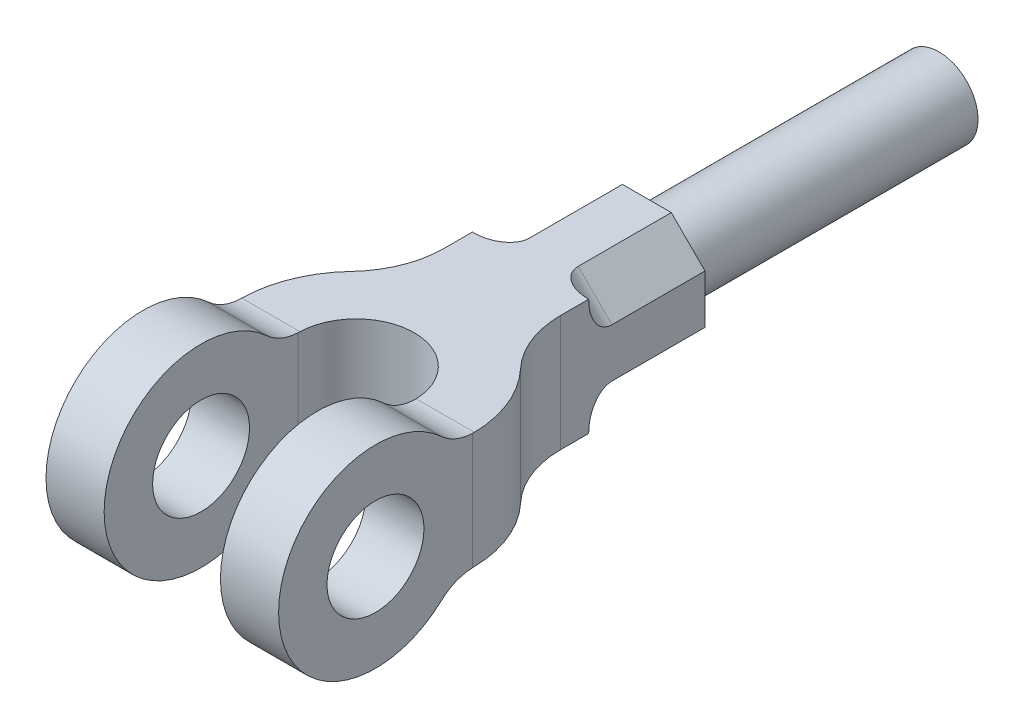
SolidWorks part; units mm, degrees
ref_plane "Front Plane" through (0, 0, 0) normal (0, 0, 1) x (1, 0, 0)
ref_plane "Top Plane" through (0, 0, 0) normal (0, 1, 0) x (1, 0, 0)
ref_plane "Right Plane" through (0, 0, 0) normal (1, 0, 0) x (0, 0, -1)
sketch "Sketch1" plane through (0, 0, 0) normal (0, 1, 0) x (1, 0, 0)
  line L1 (0, 0) -> (120, 0)
  line L2 (0, 0) -> (0, -250)
  line L3 (0, -250) -> (120, -250)
  line L4 (120, 0) -> (120, -250)
  dimension "D1" = 120
  dimension "D2" = 250
extrude "Boss-Extrude1" add sketch "Sketch1" along normal blind 100
sketch "Sketch2" plane through (0, 100, 0) normal (0, 1, 0) x (1, 0, 0)
  line L0 (60, 0) -> (60, -247.1801) construction
  line L1 (120, 0) -> (0, 0) construction
  line L2 (30, 0) -> (30, -74.5017)
  line L3 (90, 0) -> (90, -74.5017)
  line L4 (30, -150) -> (30, -250)
  line L5 (90, -150) -> (90, -250)
  line L8 (0, 0) -> (0, -250)
  line L9 (0, -250) -> (120, -250)
  line L10 (120, -250) -> (120, 0)
  line L11 (120, 0) -> (0, 0)
  line L12 (0, 0) -> (0, -250)
  line L13 (0, -250) -> (120, -250)
  line L14 (120, -250) -> (120, 0)
  line L15 (120, 0) -> (0, 0)
  arc A0 (16.3636, -108.8191) -> (103.6364, -108.8191) centre (60, -150) ccw
  arc A1 (90, -150) -> (30, -150) centre (60, -150) ccw
  arc A2 (90, -74.5017) -> (103.6364, -108.8191) centre (140, -74.5017) ccw
  arc A3 (30, -74.5017) -> (16.3636, -108.8191) centre (-20, -74.5017) cw
  point P15 (90, -98.0385)
  point P19 (30, -98.0385)
  dimension "D1" = 120
  dimension "D2" = 60
  dimension "D6" = 50
  dimension "D3" = 150
  dimension "D4" = 30
  dimension "D5" = 0
extrude "Cut-Extrude1" cut sketch "Sketch2" against normal through all
sketch "Sketch4" plane through (120, 0, 0) normal (1, 0, 0) x (0, 0, -1)
  line L0 (-250, 100) -> (-150, 100) construction
  line L1 (-250, 100) -> (-250, 0) construction
  line L2 (-250, 0) -> (-150, 0) construction
  line L3 (-200, 50) -> (0, 50) construction
  line L4 (0, 0) -> (0, 100) construction
  line L5 (-200, 100) -> (-150, 100)
  line L6 (-149.0098, 80) -> (0, 80)
  line L8 (-149.0098, 20) -> (0, 20)
  line L9 (0, 80) -> (0, 20)
  line L10 (0, 0) -> (-74.5017, 0) construction
  line L11 (0, 100) -> (-74.5017, 100) construction
  line L12 (-74.5017, 100) -> (-108.8191, 100) construction
  line L13 (-200, 0) -> (-150, 0)
  line L14 (-150, 0) -> (-108.8191, 0)
  line L15 (-108.8191, 0) -> (-74.5017, 0)
  line L16 (-108.8191, 100) -> (-150, 100) construction
  line L17 (-200, 100) -> (-250, 100)
  line L18 (-250, 100) -> (-250, 0)
  line L19 (-250, 0) -> (-200, 0)
  line L20 (0, 0) -> (-74.5017, 0)
  line L21 (0, 100) -> (-74.5017, 100)
  line L22 (-74.5017, 100) -> (-108.8191, 100)
  line L23 (-108.8191, 100) -> (-150, 100)
  line L24 (0, 0) -> (0, 100)
  arc A0 (-166.0065, 86.6667) -> (-166.0065, 13.3333) centre (-200, 50) ccw
  circle A1 centre (-200, 50) radius 25
  arc A2 (-166.0065, 13.3333) -> (-149.0098, 20) centre (-149.0098, -5) cw
  arc A3 (-149.0098, 80) -> (-166.0065, 86.6667) centre (-149.0098, 105) cw
  line M10 (-250, 0) -> (-150, 0)
  line M11 (-150, 0) -> (-150, 100)
  line M12 (-150, 100) -> (-250, 100)
  line M13 (-250, 100) -> (-250, 0)
  dimension "D1" = 50
  dimension "D3" = 25
  dimension "D2" = 60
extrude "Cut-Extrude2" cut sketch "Sketch4" against normal through all contours A0 M12 M13 | A3 A0 M11 M12 | A3 L6 L24 L21 L22 L23 M11 | A0 L18 M10 | A2 A0 M10 M11 | A2 L14 L15 L20 L24 L8 M11
sketch "Sketch5" plane through (120, 0, 0) normal (1, 0, 0) x (0, 0, -1)
  circle A0 centre (-200, 50) radius 25
  dimension "D1" = 50
extrude "Cut-Extrude3" cut sketch "Sketch5" against normal through all
sketch "Sketch6" plane through (0, 0, 0) normal (0, 0, -1) x (-1, 0, 0)
  line L0 (-30, 80) -> (-30, 62.6)
  line L1 (-30, 20) -> (-30, 80) construction
  line L2 (-30, 62.6) -> (-47.4, 80)
  line L3 (-30, 80) -> (-90, 80) construction
  line L4 (-47.4, 80) -> (-30, 80)
  line L5 (-30, 80) -> (-90, 20) construction
  line L6 (-90, 80) -> (-30, 20) construction
  line L7 (-30, 20) -> (-30, 80) construction
  line L8 (-30.5605, 20.3363) -> (-47.9605, 20.3363)
  line L9 (-30.5605, 37.7363) -> (-30.5605, 20.3363)
  line L10 (-47.9605, 20.3363) -> (-30.5605, 37.7363)
  line L11 (-90.2242, 20.8967) -> (-90.2242, 38.2967)
  line L12 (-72.8242, 20.8967) -> (-90.2242, 20.8967)
  line L13 (-90.2242, 38.2967) -> (-72.8242, 20.8967)
  line L14 (-89.6637, 80.5605) -> (-72.2637, 80.5605)
  line L15 (-89.6637, 63.1605) -> (-89.6637, 80.5605)
  line L16 (-72.2637, 80.5605) -> (-89.6637, 63.1605)
  circle A0 centre (-60.1121, 50.4484) radius 22.6425
  point P30 (-60.1121, 50.4484)
  line M6 (-30, 20) -> (-30, 80)
  line M7 (-30, 80) -> (-90, 80)
  dimension "D1" = 17.4
  dimension "D2" = 17.4
  dimension "D3" = 4
extrude "Cut-Extrude5" cut sketch "Sketch6" against normal blind 60 contours L2 M6 M7
sketch "Sketch7" plane through (0, 0, 0) normal (0, 0, -1) x (-1, 0, 0)
  line L0 (-72.6, 80) -> (-90, 80)
  line L1 (-47.4, 80) -> (-90, 80) construction
  line L2 (-90, 80) -> (-90, 62.6)
  line L3 (-90, 20) -> (-90, 80) construction
  line L4 (-90, 62.6) -> (-72.6, 80)
  dimension "D1" = 17.4
  dimension "D2" = 17.4
extrude "Cut-Extrude6" cut sketch "Sketch7" against normal blind 60
sketch "Sketch8" plane through (0, 0, 0) normal (0, 0, -1) x (-1, 0, 0)
  line L0 (-90, 37.4) -> (-90, 20)
  line L1 (-90, 20) -> (-90, 62.6) construction
  line L2 (-90, 20) -> (-72.6, 20)
  line L3 (-30, 20) -> (-90, 20) construction
  line L4 (-72.6, 20) -> (-90, 37.4)
  dimension "D1" = 17.4
  dimension "D2" = 17.4
extrude "Cut-Extrude7" cut sketch "Sketch8" against normal blind 60
sketch "Sketch9" plane through (0, 0, 0) normal (0, 0, -1) x (-1, 0, 0)
  line L0 (-30, 37.4) -> (-30, 20)
  line L1 (-30, 20) -> (-30, 80) construction
  line L2 (-30, 20) -> (-47.4, 20)
  line L3 (-30, 20) -> (-72.6, 20) construction
  line L4 (-47.4, 20) -> (-30, 37.4)
  dimension "D1" = 17.4
  dimension "D2" = 17.4
extrude "Cut-Extrude8" cut sketch "Sketch9" against normal blind 60
sketch "Sketch10" plane through (0, 0, 0) normal (0, 0, -1) x (-1, 0, 0)
  line L0 (-30, 37.4) -> (-30, 62.6) construction
  line L1 (-47.4, 80) -> (-72.6, 80) construction
  circle A0 centre (-60, 50) radius 20.1765
  dimension "D1" = 40.353
  dimension "D2" = 30
  dimension "D3" = 30
extrude "Boss-Extrude2" add sketch "Sketch10" along normal blind 150.7
fillet "Fillet1" radius 12 1 edges at (81.3, 28.7, 60)
fillet "Fillet2" radius 12 1 edges at (81.3, 71.3, 60)
fillet "Fillet3" radius 12 1 edges at (38.7, 71.3, 60)
fillet "Fillet4" radius 12 1 edges at (38.7, 28.7, 60)
